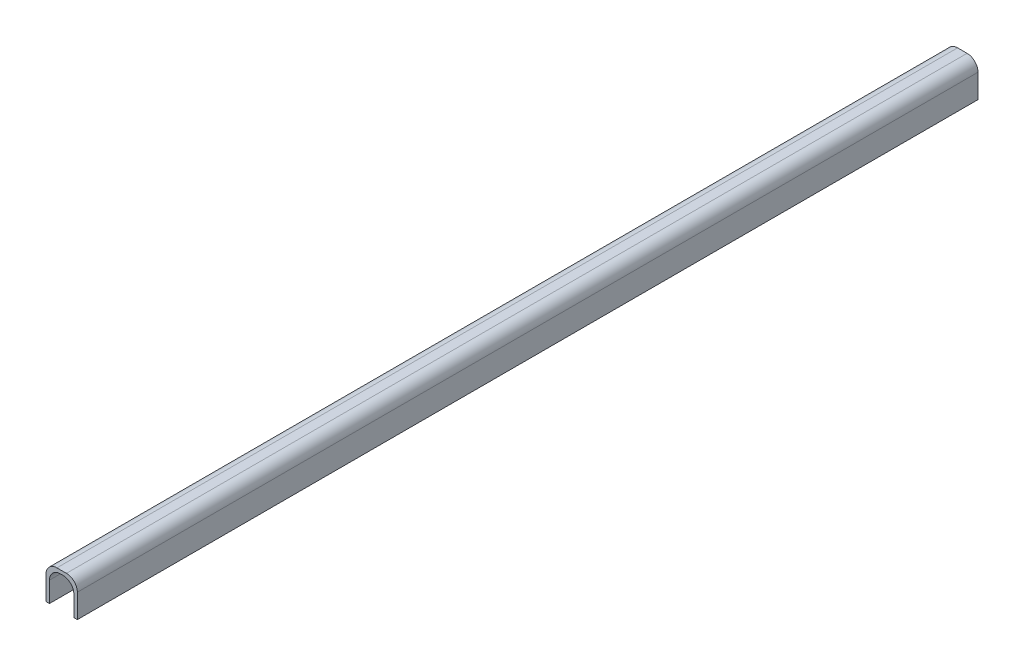
SolidWorks part; units mm, degrees
material "5052-H32"
ref_plane "Front" through (0, 0, 0) normal (0, 0, 1) x (1, 0, 0)
ref_plane "Top" through (0, 0, 0) normal (0, 1, 0) x (1, 0, 0)
ref_plane "Right" through (0, 0, 0) normal (1, 0, 0) x (0, 0, -1)
sketch "Sketch1" plane through (0, 0, 0) normal (0, 0, 1) x (1, 0, 0)
  line L0 (3.175, 0) -> (3.175, 18.575)
  line L1 (13.175, 28.575) -> (15.527, 28.575)
  line L2 (0, 0) -> (0, 21.75)
  line L3 (10, 31.75) -> (18.702, 31.75)
  line L4 (28.702, 0) -> (28.702, 21.75)
  line L5 (25.527, 0) -> (25.527, 18.575)
  line L6 (0, 0) -> (3.175, 0)
  line L7 (0, 0) -> (0, 31.75) construction
  line L8 (28.702, 0) -> (25.527, 0)
  line L9 (0, 31.75) -> (28.702, 31.75) construction
  line L10 (28.702, 0) -> (28.702, 31.75) construction
  line L11 (3.175, 28.575) -> (25.527, 28.575) construction
  line L12 (25.527, 0) -> (25.527, 28.575) construction
  line L13 (3.175, 0) -> (3.175, 28.575) construction
  arc A0 (0, 21.75) -> (10, 31.75) centre (10, 21.75) cw
  arc A1 (28.702, 21.75) -> (18.702, 31.75) centre (18.702, 21.75) ccw
  arc A2 (15.527, 28.575) -> (25.527, 18.575) centre (15.527, 18.575) cw
  arc A3 (3.175, 18.575) -> (13.175, 28.575) centre (13.175, 18.575) cw
  point P12 (0, 31.75)
  dimension "D4" = 10
  dimension "D2" = 31.75
  dimension "D3" = 3.175
extrude "Boss-Extrude1" add sketch "Sketch1" along normal blind 825
sketch "Sketch3" plane through (28.702, 0, 0) normal (1, 0, 0) x (0, 0, -1)
  line L0 (0, 10.875) -> (-760, 10.875) construction
  line L1 (0, 0) -> (0, 21.75) construction
  line L2 (-760, 0) -> (-760, 21.75)
  line L3 (-825, 0) -> (0, 0) construction
  line L4 (-825, 21.75) -> (0, 21.75) construction
  line L6 (-760, 0) -> (-855.7045, 0)
  line L7 (-760, 0) -> (-760, 58.1361)
  line L8 (-760, 58.1361) -> (-855.7045, 58.1361)
  line L9 (-855.7045, 0) -> (-855.7045, 58.1361)
  dimension "D1" = 760
